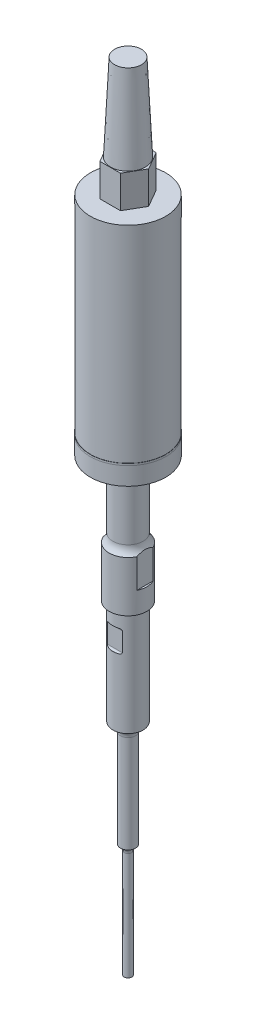
SolidWorks part; units mm, degrees
ref_plane "Front Plane" through (0, 0, 0) normal (0, 0, 1) x (1, 0, 0)
ref_plane "Top Plane" through (0, 0, 0) normal (0, 1, 0) x (1, 0, 0)
ref_plane "Right Plane" through (0, 0, 0) normal (1, 0, 0) x (0, 0, -1)
sketch "Sketch1" plane through (0, 0, 0) normal (0, 0, 1) x (1, 0, 0)
  line L0 (0, 0) -> (15.875, 0)
  line L1 (15.875, 0) -> (15.875, -95.25)
  line L2 (15.875, -95.25) -> (7.75, -95.25)
  line L3 (6.35, -99.25) -> (6.35, -123.35)
  line L5 (7.9375, -126.85) -> (7.9375, -148.15)
  line L6 (7.9375, -148.15) -> (6.35, -148.15)
  line L7 (6.35, -148.15) -> (6.35, -192.25)
  line L9 (3.15, -195.95) -> (3.15, -236.95)
  line L11 (1.6, -239.35) -> (1.6, -284.75)
  line L12 (1.6, -284.75) -> (0, -284.75)
  line L13 (0, -284.75) -> (0, 0)
  line L14 (-1.6, -239.35) -> (-1.6, -284.75) construction
  line L16 (-3.15, -195.95) -> (-3.15, -236.95) construction
  line L18 (-6.35, -148.15) -> (-6.35, -192.25) construction
  line L19 (-7.9375, -148.15) -> (-6.35, -148.15) construction
  line L20 (-7.9375, -126.85) -> (-7.9375, -148.15) construction
  line L22 (-6.35, -99.25) -> (-6.35, -123.35) construction
  line L23 (-15.875, -95.25) -> (-7.75, -95.25) construction
  line L24 (-15.875, 0) -> (-15.875, -95.25) construction
  arc A0 (6.35, -99.25) -> (7.75, -95.25) centre (12.7643, -99.25) cw
  arc A1 (-6.35, -99.25) -> (-7.75, -95.25) centre (-12.7643, -99.25) ccw construction
  arc A2 (6.35, -123.35) -> (7.9375, -126.85) centre (11.002, -123.35) ccw
  arc A3 (-6.35, -123.35) -> (-7.9375, -126.85) centre (-11.002, -123.35) cw construction
  arc A4 (1.6, -239.35) -> (3.15, -236.95) centre (4.2331, -239.35) cw
  arc A5 (-1.6, -239.35) -> (-3.15, -236.95) centre (-4.2331, -239.35) ccw construction
  arc A6 (3.15, -195.95) -> (6.35, -192.25) centre (6.8891, -195.95) cw
  arc A7 (-3.15, -195.95) -> (-6.35, -192.25) centre (-6.8891, -195.95) ccw construction
  point P34 (0, 0)
  dimension "D1" = 31.75
  dimension "D2" = 95.25
  dimension "D3" = 12.7
  dimension "D4" = 21.3
  dimension "D5" = 31.6
  dimension "D6" = 44.1
  dimension "D7" = 44.7
  dimension "D8" = 47.8
  dimension "D9" = 3.2
  dimension "D10" = 6.3
  dimension "D11" = 12.7
  dimension "D12" = 15.875
  dimension "D13" = 4
  dimension "D14" = 15.5
  dimension "D15" = 3.5
  dimension "D16" = 2.4
  dimension "D17" = 3.7
revolve "Revolve1" add sketch "Sketch1" angle 360 about L13
sketch "Sketch3" plane through (0, 0, 0) normal (0, 0, 1) x (1, 0, 0)
  line L0 (-7.9375, -126.85) -> (-7.9375, -148.15)
  line L1 (7.9375, -148.15) -> (7.9375, -126.85)
  line L2 (7.9375, -139.15) -> (7.9375, -126.85)
  line L3 (0, -17.4625) -> (0, 17.4625) construction
  line L4 (7.9375, -139.15) -> (7.1438, -139.15)
  line L5 (7.1438, -139.15) -> (7.1437, -125.949)
  line L6 (-7.1438, -139.15) -> (-7.1437, -125.949)
  line L7 (-7.9375, -139.15) -> (-7.1438, -139.15)
  line L8 (-7.9375, -139.15) -> (-7.9375, -126.85)
  arc A0 (-7.9375, -126.85) -> (-6.35, -123.35) centre (-11.002, -123.35) ccw
  arc A1 (6.35, -123.35) -> (7.9375, -126.85) centre (11.002, -123.35) ccw
  arc A2 (7.1437, -125.949) -> (7.9375, -126.85) centre (11.002, -123.35) ccw
  arc A4 (-7.1437, -125.949) -> (-7.9375, -126.85) centre (-11.002, -123.35) cw
  dimension "D1" = 9
  dimension "D2" = 14.2875
extrude "Cut-Extrude1" cut sketch "Sketch3" against normal through all both and the other way through all
sketch "Sketch4" plane through (0, 0, 0) normal (1, 0, 0) x (0, 0, -1)
  line L0 (-6.35, -148.15) -> (-6.35, -192.25)
  line L1 (6.35, -192.25) -> (6.35, -148.15)
  line L2 (6.35, -192.25) -> (6.35, -148.15) construction
  line L3 (0, 17.4625) -> (0, -17.4625) construction
  line L4 (6.35, -163.5805) -> (6.2245, -163.5805)
  line L5 (6.35, -163.5805) -> (6.35, -154.1825)
  line L6 (6.35, -154.1825) -> (6.2245, -154.1825)
  line L7 (5.5245, -162.8805) -> (5.5245, -154.8825)
  line L8 (-5.5245, -162.8805) -> (-5.5245, -154.8825)
  line L9 (-6.35, -154.1825) -> (-6.2245, -154.1825)
  line L10 (-6.35, -163.5805) -> (-6.35, -154.1825)
  line L11 (-6.35, -163.5805) -> (-6.2245, -163.5805)
  arc A0 (6.2245, -163.5805) -> (5.5245, -162.8805) centre (6.2245, -162.8805) cw
  arc A1 (5.5245, -154.8825) -> (6.2245, -154.1825) centre (6.2245, -154.8825) cw
  arc A2 (-5.5245, -154.8825) -> (-6.2245, -154.1825) centre (-6.2245, -154.8825) ccw
  arc A3 (-6.2245, -163.5805) -> (-5.5245, -162.8805) centre (-6.2245, -162.8805) ccw
  point P22 (-5.5245, -158.8815)
  dimension "D1" = 0.7
  dimension "D2" = 9.398
  dimension "D3" = 11.049
  dimension "D4" = 6.0325
extrude "Cut-Extrude2" cut sketch "Sketch4" against normal through all both and the other way through all
sketch "Sketch5" plane through (0, 0, 0) normal (0, 1, 0) x (1, 0, 0)
  line L1 (-4.3371, 7.5121) -> (-8.6742, 0)
  line L2 (-8.6742, 0) -> (-4.3371, -7.512)
  line L3 (-4.3371, -7.512) -> (4.3371, -7.512)
  line L4 (4.3371, -7.512) -> (8.6742, 0)
  line L5 (8.6742, 0) -> (4.3371, 7.512)
  line L6 (4.3371, 7.512) -> (-4.3371, 7.5121)
  circle A0 centre (0, 0) radius 7.512 construction
  dimension "D1" = 15.0241
extrude "Boss-Extrude1" add sketch "Sketch5" along normal blind 13.7
sketch "Sketch6" plane through (0, 0, 0) normal (0, 0, 1) x (1, 0, 0)
  line L0 (8.6742, 13.7) -> (-8.6742, 13.7)
  line L1 (7.35, 13.7) -> (0, 13.7)
  line L2 (0, 13.7) -> (0, 50.2)
  line L3 (0, 50.2) -> (5.65, 50.2)
  line L4 (5.65, 50.2) -> (7.35, 13.7)
  dimension "D1" = 5.65
  dimension "D2" = 7.35
  dimension "D3" = 36.5
revolve "Revolve2" add sketch "Sketch6" angle 360 about L2
sketch "Sketch7" plane through (0, 0, 0) normal (0, 0, 1) x (1, 0, 0)
  line L0 (15.875, -95.25) -> (15.875, 0) construction
  line L1 (15.875, -87.65) -> (15.975, -87.65)
  line L2 (15.875, -87.65) -> (15.875, -86.85)
  line L3 (15.875, -86.85) -> (15.975, -86.85)
  line L4 (15.975, -87.65) -> (15.975, -86.85)
  dimension "D1" = 7.6
  dimension "D2" = 0.8
  dimension "D3" = 0.1
revolve "Dont Clamp Below" add sketch "Sketch7" angle 360 about L13
